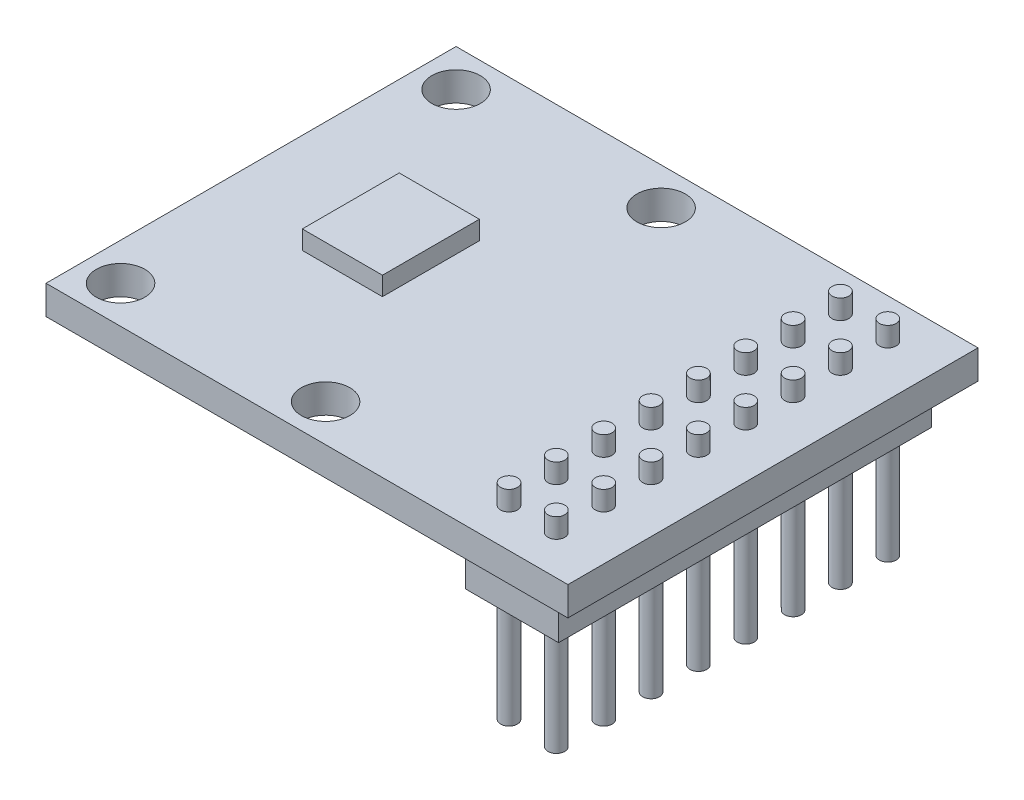
SolidWorks part; units mm, degrees
ref_plane "Front Plane" through (0, 0, 0) normal (0, 0, 1) x (1, 0, 0)
ref_plane "Top Plane" through (0, 0, 0) normal (0, 1, 0) x (1, 0, 0)
ref_plane "Right Plane" through (0, 0, 0) normal (1, 0, 0) x (0, 0, -1)
sketch "Sketch1" plane through (0, 0, 0) normal (0, 1, 0) x (1, 0, 0)
  line L0 (-12.4547, 0) -> (22.772, 0) construction
  line L1 (-7.5, 9) -> (7.5, 9) construction
  line L2 (-7.5, 11) -> (7.5, 11)
  line L3 (-7.5, 11) -> (-7.5, -11)
  line L4 (-7.5, -11) -> (7.5, -11)
  line L5 (7.5, 11) -> (7.5, -11)
  line L6 (-7.5, 11) -> (7.5, -11) construction
  line L7 (-7.5, -11) -> (7.5, 11) construction
  line L8 (0, 11) -> (0, -11) construction
  circle A0 centre (-5.5, 9) radius 1.3
  circle A1 centre (5.5, 9) radius 1.3
  circle A2 centre (5.5, -9) radius 1.3
  circle A3 centre (-5.5, -9) radius 1.3
  circle A4 centre (0, 0) radius 0.5
  point P3 (0, 0)
  dimension "D3" = 2.6
  dimension "D6" = 1
  dimension "D1" = 15
  dimension "D2" = 22
  dimension "D4" = 11
  dimension "D5" = 9
extrude "Boss-Extrude1" add sketch "Sketch1" along normal blind 1.55
sketch "Sketch2" plane through (0, 1.55, 0) normal (0, 1, 0) x (1, 0, 0)
  line L1 (-2.15, 2.6) -> (2.15, 2.6)
  line L2 (-2.15, 2.6) -> (-2.15, -2.6)
  line L3 (-2.15, -2.6) -> (2.15, -2.6)
  line L4 (2.15, 2.6) -> (2.15, -2.6)
  line L5 (-2.15, 2.6) -> (2.15, -2.6) construction
  line L6 (-2.15, -2.6) -> (2.15, 2.6) construction
  point P0 (0, 0)
  dimension "D1" = 4.3
  dimension "D2" = 5.2
extrude "Boss-Extrude2" add sketch "Sketch2" along normal blind 1
sketch "Sketch4" plane through (7.5, 0, 0) normal (1, 0, 0) x (0, 0, -1)
  line L4 (-11, 0) -> (11, 0)
  line L5 (11, 0) -> (11, 1.55)
  line L6 (11, 1.55) -> (-11, 1.55)
  line L7 (-11, 1.55) -> (-11, 0)
  line L8 (-11, 0) -> (11, 0)
  line L9 (11, 0) -> (11, 1.55)
  line L10 (11, 1.55) -> (-11, 1.55)
  line L11 (-11, 1.55) -> (-11, 0)
  dimension "D1" = 0
extrude "Boss-Extrude3" add sketch "Sketch4" along normal blind 13
sketch "Sketch6" plane through (0, 0, 0) normal (0, -1, 0) x (1, 0, 0)
  line L0 (16.5, 11) -> (16.5, -11) construction
  line L1 (-7.5, 11) -> (20.5, 11) construction
  line L2 (20.5, -11) -> (-7.5, -11) construction
  line L3 (20.5, 11) -> (20.5, -11) construction
  line L5 (14, 10) -> (19, 10)
  line L6 (14, 10) -> (14, -10)
  line L7 (14, -10) -> (19, -10)
  line L8 (19, 10) -> (19, -10)
  line L9 (14, 10) -> (19, -10) construction
  line L10 (14, -10) -> (19, 10) construction
  point P8 (16.5, 0)
  dimension "D1" = 4
  dimension "D2" = 20
  dimension "D3" = 5
extrude "Boss-Extrude4" add sketch "Sketch6" along normal blind 2.4
sketch "Sketch7" plane through (0, -2.4, 0) normal (0, -1, 0) x (1, 0, 0)
  line L0 (16.5, 10) -> (16.5, -10) construction
  line L1 (19, 10) -> (14, 10) construction
  line L2 (14, -10) -> (19, -10) construction
  line L3 (15.23, 10) -> (15.23, -10) construction
  line L4 (17.77, 10) -> (17.77, -10) construction
  line L5 (14, 0) -> (19, 0) construction
  line L6 (14, 10) -> (14, -10) construction
  line L7 (19, -10) -> (19, 10) construction
  circle A0 centre (15.23, 1.27) radius 0.45
  dimension "D3" = 0.9
  dimension "D1" = 2.54
  dimension "D2" = 1.27
extrude "Boss-Extrude5" add sketch "Sketch7" along normal blind 6 and the other way blind 5
pattern_linear "LPattern1" count 4 spacing 2.54 along (0, 0, 1) count 2 spacing 2.54 along (1, 0, 0) of "Boss-Extrude5"
mirror "Mirror1" about plane through (0, 0, 0) normal (0, 0, 1) of "LPattern1", "Boss-Extrude5"
